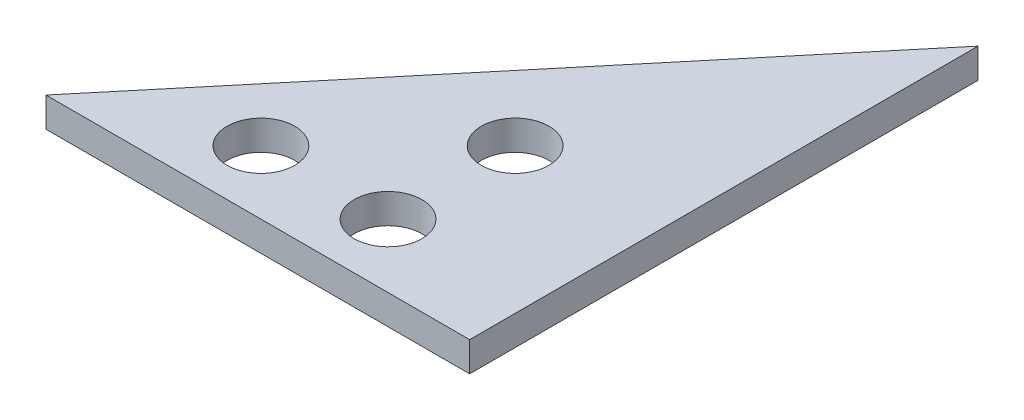
SolidWorks part; units mm, degrees
material "Plain Carbon Steel"
ref_plane "Front Plane" through (0, 0, 0) normal (0, 0, 1) x (1, 0, 0)
ref_plane "Top Plane" through (0, 0, 0) normal (0, 1, 0) x (1, 0, 0)
ref_plane "Right Plane" through (0, 0, 0) normal (1, 0, 0) x (0, 0, -1)
sketch "Sketch1" plane through (0, 0, 0) normal (0, 1, 0) x (1, 0, 0)
  line L0 (-2.7653, -5.6756) -> (47.2347, -5.6756)
  line L1 (47.2347, -5.6756) -> (47.2347, 54.3244)
  line L2 (47.2347, 54.3244) -> (-2.7653, -5.6756)
  dimension "D1" = 60
  dimension "D2" = 50
  dimension "D3" = 50.194
extrude "Boss-Extrude1" add sketch "Sketch1" along normal blind 3.5
sketch "Sketch2" plane through (0, 3.5, 0) normal (0, 1, 0) x (1, 0, 0)
  line L0 (-2.7653, -5.6756) -> (47.2347, -5.6756) construction
  line L1 (47.2347, -5.6756) -> (47.2347, 54.3244) construction
  circle A0 centre (30.102, 1.8244) radius 4
  circle A2 centre (15.102, 1.8244) radius 4
  circle A3 centre (30.102, 16.8244) radius 4
  dimension "D1" = 7.5
  dimension "D4" = 17.1328
  dimension "D2" = 15
  dimension "D3" = 15
  dimension "D5" = 17.1328
  dimension "D6" = 7.5
extrude "Cut-Extrude1" cut sketch "Sketch2" against normal up to surface (3.5 mm away) up to face at (30.5681, 0, -14.3244)
